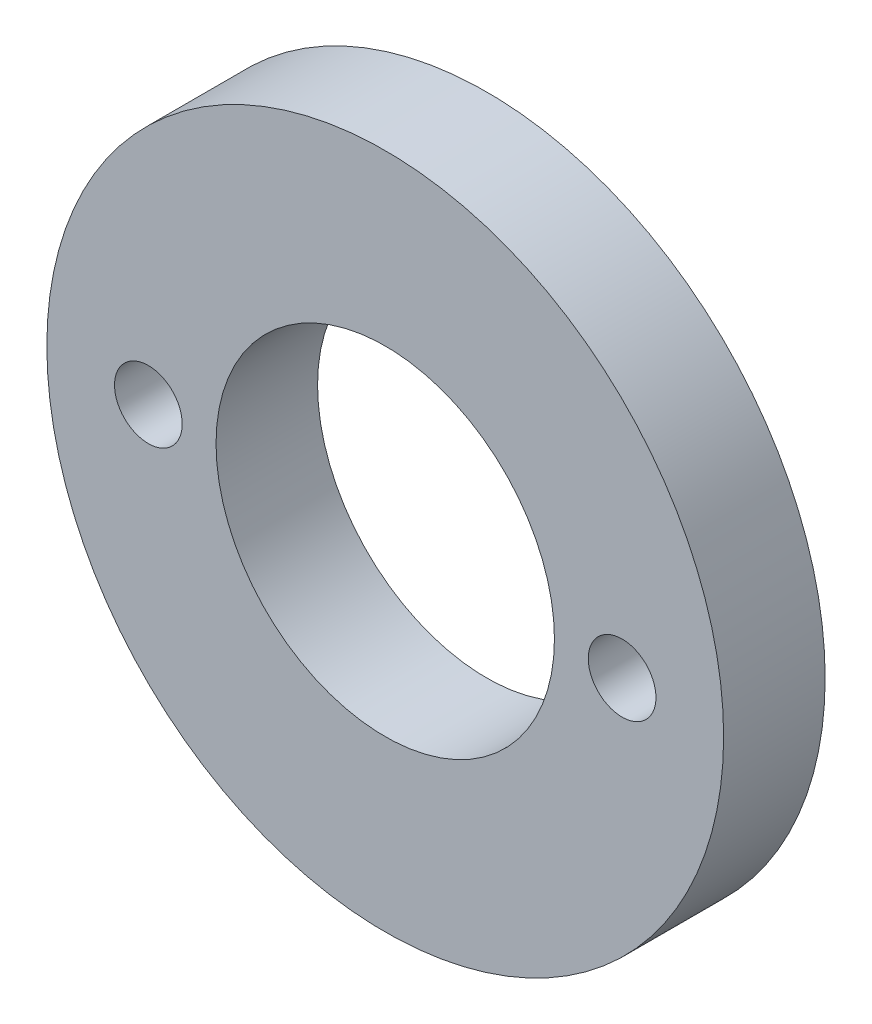
SolidWorks part; units mm, degrees
material "Acrylic (Medium-high impact)"
ref_plane "Front Plane" through (0, 0, 0) normal (0, 0, 1) x (1, 0, 0)
ref_plane "Top Plane" through (0, 0, 0) normal (0, 1, 0) x (1, 0, 0)
ref_plane "Right Plane" through (0, 0, 0) normal (1, 0, 0) x (0, 0, -1)
sketch "Sketch1" plane through (0, 0, 0) normal (0, 0, 1) x (1, 0, 0)
  circle A0 centre (0, 0) radius 5
  circle A1 centre (0, 0) radius 10
  dimension "spacer_ID" = 10
  dimension "spacer_OD" = 20
extrude "Boss-Extrude1" add sketch "Sketch1" along normal mid plane 3
sketch "Sketch2" plane through (0, 0, 1.5) normal (0, 0, 1) x (1, 0, 0)
  line L0 (0, 9) -> (0, 5) construction
  line L1 (0, 0) -> (0, 5) construction
  line L2 (-1.6, 4.7371) -> (-1.6, 9)
  line L3 (-1.6, 9) -> (1.6, 9)
  line L4 (1.6, 4.7371) -> (1.6, 9)
  circle A1 centre (0, 0) radius 5 construction
  arc A4 (-1.6, 4.7371) -> (1.6, 4.7371) centre (0, 0) cw
  dimension "spacer_key_width" = 3.2
  dimension "spacer_key_height" = 2.2
extrude "Keyway-Cut" [suppressed] cut sketch "Sketch2" against normal through all both
sketch "Sketch3" plane through (0, 0, 1.5) normal (0, 0, 1) x (1, 0, 0)
  circle A1 centre (0, 0) radius 7 construction
  circle A2 centre (-7, 0) radius 1
  dimension "D1" = 14
  dimension "D2" = 2
extrude "AlignmentHole-Cut" cut sketch "Sketch3" against normal through all contours A2
pattern_circular "CirPattern1" count 2 over 360 about axis through (0, 0, 0) along (0, 0, 1) of "AlignmentHole-Cut", "Keyway-Cut"
equation "\"OD\"=20"
equation "\"ID\"=10"
equation "\"Key_Width\"=3.2"
equation "\"Key_Height\"=4"
equation "\"spacer_ID@Sketch1\"= \"ID\""
equation "\"spacer_OD@Sketch1\"= \"OD\""
equation "\"spacer_key_width@Sketch2\"= \"Key_Width\""
equation "\"spacer_key_height@Sketch2\"= \"Key_Height\""
equation "\"Alignment_Pin_OD\"=2"
equation "\"Alignment_Pin_PCD\"=14"
equation "\"D1@Sketch3\"=\"Alignment_Pin_PCD\""
equation "\"D2@Sketch3\"=\"Alignment_Pin_OD\""
equation "\"Spacer_Thickness\"=3"
equation "\"D1@Boss-Extrude1\"= \"Spacer_Thickness\""
